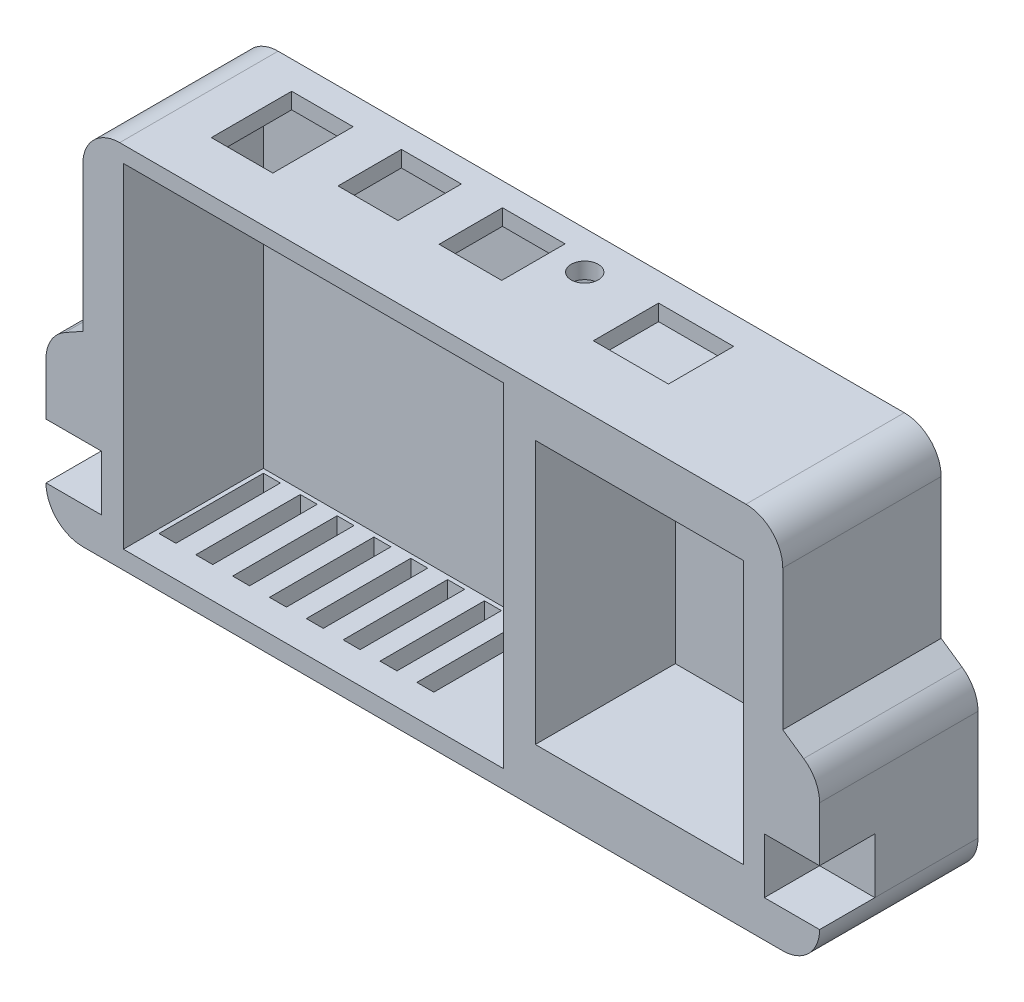
SolidWorks part; units mm, degrees
material "ABS"
ref_plane "前视基准面" through (0, 0, 0) normal (0, 0, 1) x (1, 0, 0)
ref_plane "上视基准面" through (0, 0, 0) normal (0, 1, 0) x (1, 0, 0)
ref_plane "右视基准面" through (0, 0, 0) normal (1, 0, 0) x (0, 0, -1)
other "Configuration Table"
sketch "草图1" plane through (0, 0, 0) normal (0, 0, 1) x (1, 0, 0)
  line L0 (0, 10) -> (0, 39.1866)
  line L1 (5.1248, 47.9177) -> (10, 50.6399)
  line L2 (10, 50.6399) -> (10, 90)
  line L3 (20, 100) -> (190, 100)
  line L4 (200, 90) -> (200, 51.9634)
  line L5 (200, 51.9634) -> (205.6833, 48.0378)
  line L6 (210, 39.8098) -> (210, 10)
  line L7 (200, 0) -> (10, 0)
  line L9 (21.0146, 95.6225) -> (124.2146, 95.6225)
  line L10 (21.0146, 95.6225) -> (21.0146, 4.9225)
  line L11 (21.0146, 4.9225) -> (124.2146, 4.9225)
  line L12 (124.2146, 95.6225) -> (124.2146, 4.9225)
  line L13 (132.8291, 86.4254) -> (189.3291, 86.4254)
  line L14 (132.8291, 86.4254) -> (132.8291, 14.9254)
  line L15 (132.8291, 14.9254) -> (189.3291, 14.9254)
  line L16 (189.3291, 86.4254) -> (189.3291, 14.9254)
  arc A0 (210, 10) -> (200, 0) centre (200, 10) cw
  arc A1 (0, 10) -> (10, 0) centre (10, 10) ccw
  arc A2 (205.6833, 48.0378) -> (210, 39.8098) centre (200, 39.8098) cw
  arc A3 (0, 39.1866) -> (5.1248, 47.9177) centre (10, 39.1866) cw
  arc A4 (190, 100) -> (200, 90) centre (190, 90) cw
  arc A5 (10, 90) -> (20, 100) centre (20, 90) cw
  point P13 (0, 0)
  dimension "D1" = 10
  dimension "D2" = 190
  dimension "D3" = 100
  dimension "D4" = 103.2
  dimension "D5" = 90.7
  dimension "D6" = 71.5
  dimension "D7" = 56.5
  dimension "D8" = 10
  dimension "D9" = 10
extrude "凸台-拉伸1" add sketch "草图1" along normal blind 43
sketch "草图3" plane through (0, 0, 0) normal (0, 0, 1) x (1, 0, 0)
  line L0 (0, 10) -> (0, 39.1866)
  line L1 (5.1248, 47.9177) -> (10, 50.6399)
  line L2 (10, 50.6399) -> (10, 90)
  line L3 (20, 100) -> (180, 100)
  line L4 (190, 90) -> (190, 51.9634)
  line L5 (190, 51.9634) -> (195.6833, 48.0378)
  line L6 (200, 39.8098) -> (200, 10)
  line L7 (190, 0) -> (10, 0)
  arc A0 (200, 10) -> (190, 0) centre (190, 10) cw
  arc A1 (0, 10) -> (10, 0) centre (10, 10) ccw
  arc A2 (195.6833, 48.0378) -> (200, 39.8098) centre (190, 39.8098) cw
  arc A3 (0, 39.1866) -> (5.1248, 47.9177) centre (10, 39.1866) cw
  arc A4 (180, 100) -> (190, 90) centre (180, 90) cw
  arc A5 (10, 90) -> (20, 100) centre (20, 90) cw
  point P13 (0, 0)
  dimension "D1" = 10
  dimension "D2" = 180
  dimension "D3" = 100
  dimension "D8" = 10
  dimension "D9" = 10
extrude "凸台-拉伸3" add sketch "草图3" along normal blind 5
sketch "草图4" plane through (0, 100, 0) normal (0, 1, 0) x (1, 0, 0)
  line L1 (130.8683, -7.5722) -> (151.2394, -7.5722)
  line L2 (130.8683, -7.5722) -> (130.8683, -25.2818)
  line L3 (130.8683, -25.2818) -> (151.2394, -25.2818)
  line L4 (151.2394, -7.5722) -> (151.2394, -25.2818)
  line L5 (31.2602, -7.5722) -> (47.9461, -7.5722)
  line L6 (31.2602, -7.5722) -> (31.2602, -29.3765)
  line L7 (31.2602, -29.3765) -> (47.9461, -29.3765)
  line L8 (47.9461, -7.5722) -> (47.9461, -29.3765)
  line L9 (59.8207, -6.3438) -> (76.0972, -6.3438)
  line L10 (59.8207, -6.3438) -> (59.8207, -23.5415)
  line L11 (59.8207, -23.5415) -> (76.0972, -23.5415)
  line L12 (76.0972, -6.3438) -> (76.0972, -23.5415)
  line L13 (87.2552, -6.3438) -> (104.2483, -6.3438)
  line L14 (87.2552, -6.3438) -> (87.2552, -23.5415)
  line L15 (87.2552, -23.5415) -> (104.2483, -23.5415)
  line L16 (104.2483, -6.3438) -> (104.2483, -23.5415)
  circle A0 centre (113.5637, -10.3226) radius 3.6826
extrude "切除-拉伸2" cut sketch "草图4" against normal up to surface (4.3775 mm away) up to face at (72.6146, 95.6225, 24)
sketch "草图5" plane through (0, 0, 0) normal (0, -1, 0) x (1, 0, 0)
  line L0 (32.1495, 34.485) -> (32.1495, 6.1292)
  line L1 (22.1495, 34.485) -> (26.756, 34.485)
  line L2 (22.1495, 34.485) -> (22.1495, 6.1292)
  line L3 (22.1495, 6.1292) -> (26.756, 6.1292)
  line L4 (26.756, 34.485) -> (26.756, 6.1292)
  line L5 (32.1495, 34.485) -> (36.756, 34.485)
  line L6 (36.756, 34.485) -> (36.756, 6.1292)
  line L7 (32.1495, 6.1292) -> (36.756, 6.1292)
  line L8 (42.1495, 34.485) -> (42.1495, 6.1292)
  line L9 (42.1495, 34.485) -> (46.756, 34.485)
  line L10 (46.756, 34.485) -> (46.756, 6.1292)
  line L11 (42.1495, 6.1292) -> (46.756, 6.1292)
  line L12 (52.1495, 34.485) -> (52.1495, 6.1292)
  line L13 (52.1495, 34.485) -> (56.756, 34.485)
  line L14 (56.756, 34.485) -> (56.756, 6.1292)
  line L15 (52.1495, 6.1292) -> (56.756, 6.1292)
  line L16 (62.1495, 34.485) -> (62.1495, 6.1292)
  line L17 (62.1495, 34.485) -> (66.756, 34.485)
  line L18 (66.756, 34.485) -> (66.756, 6.1292)
  line L19 (62.1495, 6.1292) -> (66.756, 6.1292)
  line L20 (72.1495, 34.485) -> (72.1495, 6.1292)
  line L21 (72.1495, 34.485) -> (76.756, 34.485)
  line L22 (76.756, 34.485) -> (76.756, 6.1292)
  line L23 (72.1495, 6.1292) -> (76.756, 6.1292)
  line L24 (82.1495, 34.485) -> (82.1495, 6.1292)
  line L25 (82.1495, 34.485) -> (86.756, 34.485)
  line L26 (86.756, 34.485) -> (86.756, 6.1292)
  line L27 (82.1495, 6.1292) -> (86.756, 6.1292)
  line L28 (92.1495, 34.485) -> (92.1495, 6.1292)
  line L29 (92.1495, 34.485) -> (96.756, 34.485)
  line L30 (96.756, 34.485) -> (96.756, 6.1292)
  line L31 (92.1495, 6.1292) -> (96.756, 6.1292)
  dimension "D1" = 8
extrude "切除-拉伸3" cut sketch "草图5" against normal up to surface (4.9225 mm away) up to face at (72.6146, 4.9225, 24)
sketch "草图7" plane through (0, 0, 43) normal (0, 0, 1) x (1, 0, 0)
  line L0 (6, 30) -> (16, 30) construction
  line L1 (6, 30) -> (6, 20) construction
  line L2 (0, 39.1866) -> (0, 10) construction
  line L3 (10, 0) -> (200, 0) construction
  line L4 (210, 10) -> (210, 39.8098) construction
  line L6 (194, 30) -> (204, 30) construction
  line L7 (194, 30) -> (194, 20) construction
  circle A11 centre (6, 30) radius 1.6
  circle A12 centre (16, 30) radius 1.6
  circle A13 centre (16, 20) radius 1.6
  circle A14 centre (6, 20) radius 1.6
  circle A19 centre (194, 30) radius 1.6
  circle A20 centre (204, 30) radius 1.6
  circle A21 centre (204, 20) radius 1.6
  circle A22 centre (194, 20) radius 1.6
  dimension "D1" = 3.2
  dimension "D4" = 6
  dimension "D6" = 30
  dimension "D9" = 3.2
  dimension "D2" = 10
  dimension "D3" = 10
  dimension "D5" = 30
  dimension "D7" = 6
  dimension "D8" = 10
  dimension "D10" = 10
  dimension "D11" = 10
extrude "切除-拉伸4" [suppressed] cut sketch "草图7" against normal through all
sketch "草图8" plane through (0, 0, 0) normal (-1, 0, 0) x (0, 0, 1)
  line L0 (43, 10) -> (0, 10) construction
  line L1 (28, 25) -> (43, 25)
  line L2 (28, 25) -> (28, 10)
  line L3 (28, 10) -> (43, 10)
  line L4 (43, 25) -> (43, 10)
  dimension "D1" = 15
  dimension "D2" = 15
extrude "切除-拉伸5" cut sketch "草图8" against normal blind 15
ref_plane "基准面1" through (105, 0, 0) normal (-1, 0, 0) x (0, 0, 1)
mirror "镜向1" about plane through (105, 0, 0) normal (-1, 0, 0) of "切除-拉伸5"
